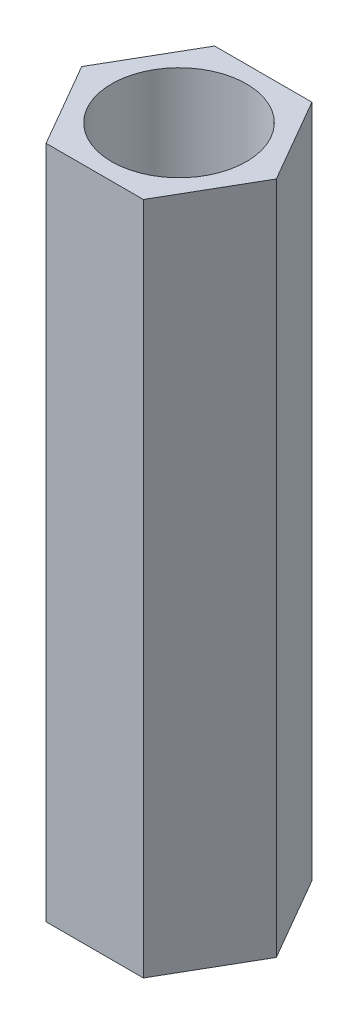
SolidWorks part; units mm, degrees
material "6061 合金"
ref_plane "前视基准面" through (0, 0, 0) normal (0, 0, 1) x (1, 0, 0)
ref_plane "上视基准面" through (0, 0, 0) normal (0, 1, 0) x (1, 0, 0)
ref_plane "右视基准面" through (0, 0, 0) normal (1, 0, 0) x (0, 0, -1)
sketch "草图1" plane through (0, 0, 0) normal (0, 1, 0) x (1, 0, 0)
  line L1 (1.4434, 2.5) -> (-1.4434, 2.5)
  line L2 (-1.4434, 2.5) -> (-2.8868, 0)
  line L3 (-2.8868, 0) -> (-1.4434, -2.5)
  line L4 (-1.4434, -2.5) -> (1.4434, -2.5)
  line L5 (1.4434, -2.5) -> (2.8868, 0)
  line L6 (2.8868, 0) -> (1.4434, 2.5)
  circle A0 centre (0, 0) radius 2.5 construction
  circle A1 centre (0, 0) radius 2
  dimension "D1" = 5
  dimension "D2" = 4
extrude "凸台-拉伸1" add sketch "草图1" along normal blind 20
